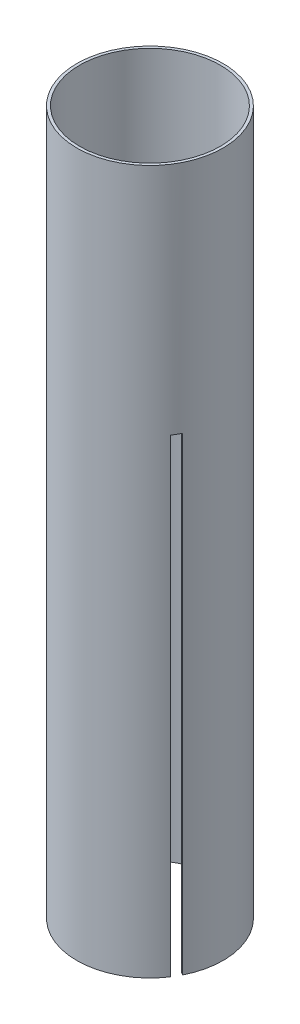
SolidWorks part; units mm, degrees
material "S-Glass Fiber"
ref_plane "Front Plane" through (0, 0, 0) normal (0, 0, 1) x (1, 0, 0)
ref_plane "Top Plane" through (0, 0, 0) normal (0, 1, 0) x (1, 0, 0)
ref_plane "Right Plane" through (0, 0, 0) normal (1, 0, 0) x (0, 0, -1)
sketch "Sketch1" plane through (0, 0, 0) normal (0, 1, 0) x (1, 0, 0)
  circle A0 centre (0, 0) radius 39.624
  circle A1 centre (0, 0) radius 38.1
  dimension "D1" = 79.248
  dimension "D2" = 76.2
extrude "Boss-Extrude1" add sketch "Sketch1" along normal blind 381
sketch "Sketch2" plane through (0, 0, 0) normal (0, 0, 1) x (1, 0, 0)
  line L0 (-2.3813, 0) -> (2.3812, 0)
  line L1 (-39.624, 0) -> (39.624, 0) construction
  line L2 (2.3812, 0) -> (2.3812, 254)
  line L3 (2.3812, 254) -> (-2.3813, 254)
  line L4 (-2.3813, 254) -> (-2.3813, -1.7067)
  point P6 (0, 0)
  dimension "D1" = 4.7625
  dimension "D2" = 254
extrude "Cut-Extrude1" cut sketch "Sketch2" against normal through all contours L3 L4 L0 L2
pattern_circular "CirPattern1" count 3 over 360 about axis through (0, 0, 0) along (0, 1, 0) of "Cut-Extrude1"
